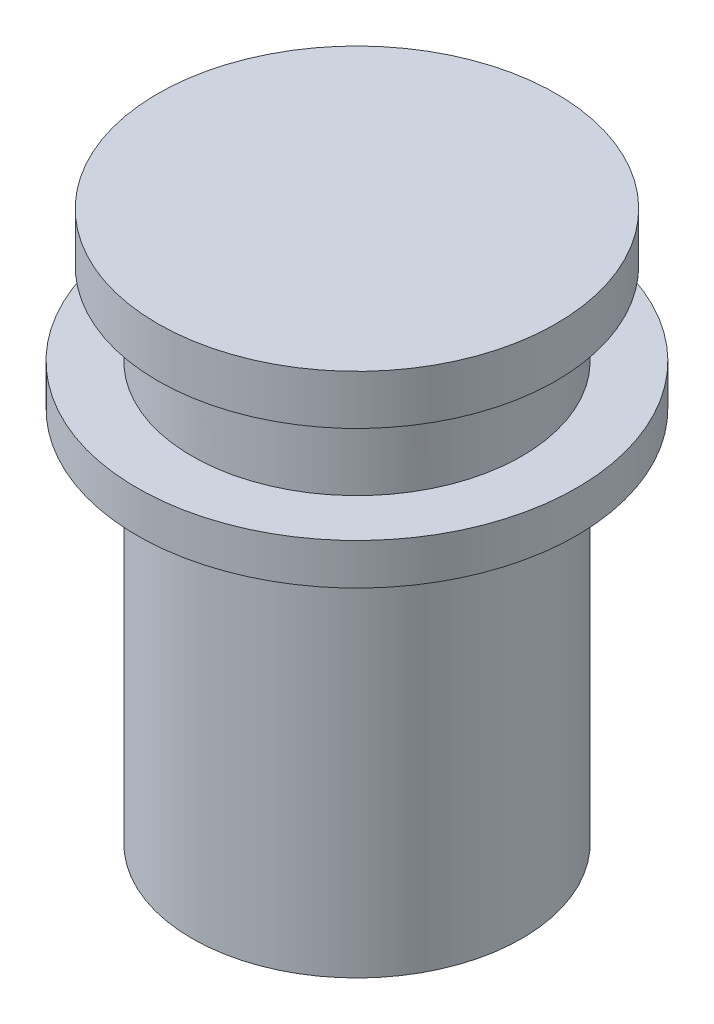
SolidWorks part; units mm, degrees
ref_plane "Front Plane" through (0, 0, 0) normal (0, 0, 1) x (1, 0, 0)
ref_plane "Top Plane" through (0, 0, 0) normal (0, 1, 0) x (1, 0, 0)
ref_plane "Right Plane" through (0, 0, 0) normal (1, 0, 0) x (0, 0, -1)
other "Configuration Table"
sketch "草图1" plane through (0, 0, 0) normal (0, 1, 0) x (1, 0, 0)
  circle A0 centre (0, 0) radius 6
extrude "凸台-拉伸1" add sketch "草图1" along normal blind 18.2
sketch "草图2" plane through (0, 18.2, 0) normal (0, 1, 0) x (1, 0, 0)
  circle A0 centre (0, 0) radius 7.25
extrude "凸台-拉伸2" add sketch "草图2" along normal blind 1.8
sketch "草图3" plane through (0, 0, 0) normal (1, 0, 0) x (0, 0, -1)
  line L0 (0, 0) -> (0, 15.2) construction
  line L1 (-6, 18.2) -> (6, 18.2) construction
  line L2 (0, 15.2) -> (-6, 15.2) construction
  line L3 (-6, 18.2) -> (-6, 0) construction
  line L4 (-6, 15.2) -> (-6, 13.7)
  line L5 (-6, 13.7) -> (-8, 13.7)
  line L6 (-8, 13.7) -> (-8, 15.2)
  line L7 (-8, 15.2) -> (-6, 15.2)
  dimension "D1" = 3
revolve "旋转1" add sketch "草图3" angle 360 about L0
